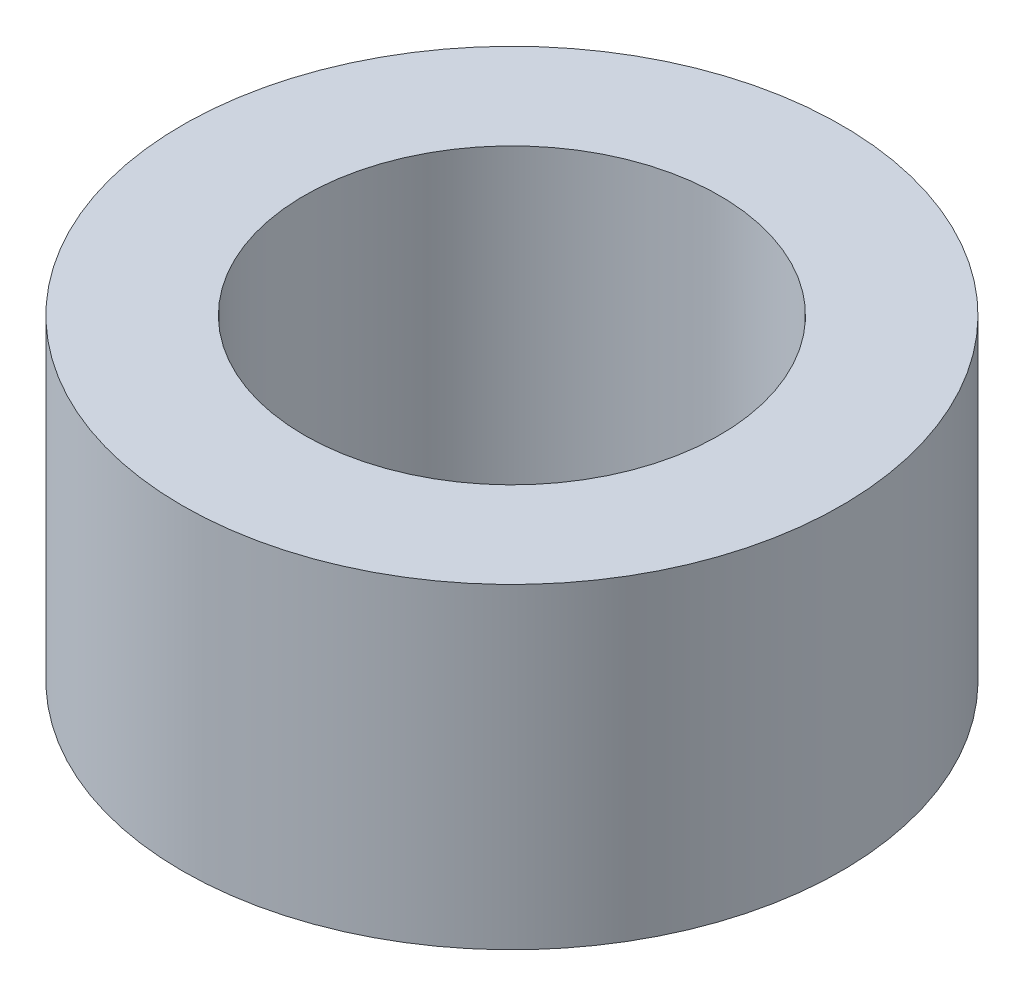
SolidWorks part; units mm, degrees
material "Custom Plastic"
ref_plane "X-Y Datum" through (0, 0, 0) normal (0, 0, 1) x (1, 0, 0)
ref_plane "X-Z Datum" through (0, 0, 0) normal (0, 1, 0) x (1, 0, 0)
ref_plane "Y-Z Datum" through (0, 0, 0) normal (1, 0, 0) x (0, 0, -1)
sketch "Sketch2" plane through (0, 0, 0) normal (0, 1, 0) x (1, 0, 0)
  circle A0 centre (0, 0) radius 3.175
  circle A1 centre (0, 0) radius 2
  dimension "D1" = 4
  dimension "D2" = 6.35
extrude "Boss-Extrude1" add sketch "Sketch2" against normal blind 3.048
